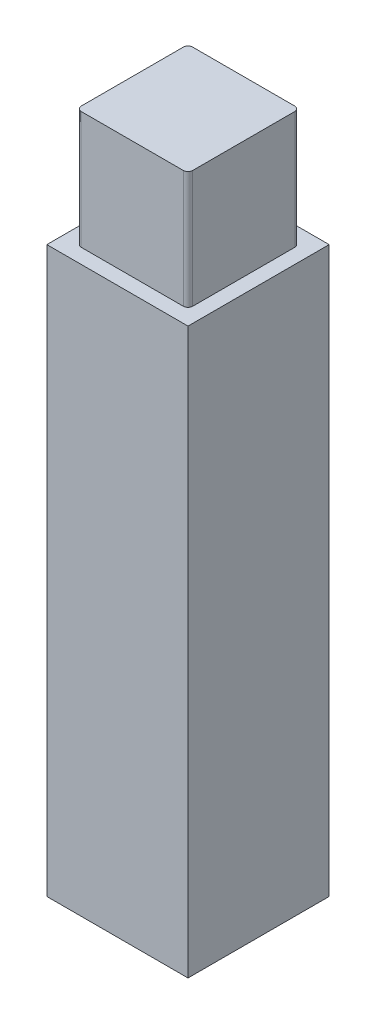
SolidWorks part; units mm, degrees
ref_plane "Front Plane" through (0, 0, 0) normal (0, 0, 1) x (1, 0, 0)
ref_plane "Top Plane" through (0, 0, 0) normal (0, 1, 0) x (1, 0, 0)
ref_plane "Right Plane" through (0, 0, 0) normal (1, 0, 0) x (0, 0, -1)
sketch "Sketch1" plane through (0, 0, 0) normal (0, 1, 0) x (1, 0, 0)
  line L1 (-15, 15) -> (15, 15)
  line L2 (-15, 15) -> (-15, -15)
  line L3 (-15, -15) -> (15, -15)
  line L4 (15, 15) -> (15, -15)
  line L5 (-15, 15) -> (15, -15) construction
  line L6 (-15, -15) -> (15, 15) construction
  point P0 (0, 0)
  dimension "D1" = 30
  dimension "D2" = 30
extrude "Boss-Extrude1" add sketch "Sketch1" along normal blind 120
sketch "Sketch2" plane through (0, 120, 0) normal (0, 1, 0) x (1, 0, 0)
  line L1 (-11.85, 11.85) -> (11.85, 11.85)
  line L2 (-11.85, 11.85) -> (-11.85, -11.85)
  line L3 (-11.85, -11.85) -> (11.85, -11.85)
  line L4 (11.85, 11.85) -> (11.85, -11.85)
  line L5 (-11.85, 11.85) -> (11.85, -11.85) construction
  line L6 (-11.85, -11.85) -> (11.85, 11.85) construction
  point P0 (0, 0)
  dimension "D1" = 23.7
  dimension "D2" = 23.7
extrude "Boss-Extrude2" add sketch "Sketch2" along normal blind 25
sketch "Sketch3" plane through (0, 0, 0) normal (0, -1, 0) x (1, 0, 0)
  line L1 (-12, 12) -> (12, 12)
  line L2 (-12, 12) -> (-12, -12)
  line L3 (-12, -12) -> (12, -12)
  line L4 (12, 12) -> (12, -12)
  line L5 (-12, 12) -> (12, -12) construction
  line L6 (-12, -12) -> (12, 12) construction
  point P0 (0, 0)
  dimension "D1" = 24
  dimension "D2" = 24
extrude "Cut-Extrude1" cut sketch "Sketch3" against normal blind 26
fillet "Fillet1" radius 1 4 edges at (-11.85, 132.5, -11.85) (-11.85, 132.5, 11.85) (11.85, 132.5, 11.85) (11.85, 132.5, -11.85)
equation "\"board_w\"= 33.8"
equation "\"board_l\"= 41"
equation "\"stack_h\"= 19.5"
equation "\"module_w\"= 9.9"
equation "\"lens_d\"= 7.8"
equation "\"lens_from_end\"= 8"
equation "\"usb_w\"= 13"
equation "\"plug_h\"= 7"
equation "\"usb_from_back\"= 6"
equation "\"clear\"= 0.4"
equation "\"wall\"= 3"
equation "\"floor_t\"= 2.5"
equation "\"pocket_clear\"= 0.3"
equation "\"lens_clear\"= 0.6"
equation "\"plate_w\"= 16"
equation "\"plate_clear\"= 0.3"
equation "\"plate_t\"= 1.2"
equation "\"plate_seat\"= 0.8"
equation "\"window_d\"= 12"
equation "\"lid_t\"= 2"
equation "\"lid_gap\"= 1"
equation "\"groove_d\"= 1.2"
equation "\"groove_clear\"= 0.15"
equation "\"lip_top\"= 1.2"
equation "\"side_clear\"= 0.2"
equation "\"slide_clear\"= 0.2"
equation "\"ball_d\"= 16"
equation "\"ball_clear\"= 0.3"
equation "\"lip\"= 1.2"
equation "\"cup_floor\"= 1.2"
equation "\"cup_d\"= 26"
equation "\"slit_w\"= 1.5"
equation "\"slit_depth\"= 9"
equation "\"lug_w\"= 16"
equation "\"m3_hole\"= 3.4"
equation "\"m3_nut\"= 5.7"
equation "\"m3_nut_d\"= 2.6"
equation "\"boss_d\"= 20"
equation "\"boss_h\"= 8"
equation "\"nut_af\"= 11.4"
equation "\"nut_t\"= 5.8"
equation "\"screw_hole\"= 6.6"
equation "\"post_w\"= 30"
equation "\"post_len\"= 120"
equation "\"spigot_w\"= 23.7"
equation "\"bore_w\"= 24"
equation "\"spigot_len\"= 25"
equation "\"base_w\"= 130"
equation "\"base_h\"= 40"
equation "\"hole_depth\"= 30"
equation "\"base_clear\"= 0.4"
equation "\"base_col\"= 42"
equation "\"base_shell\"= 3"
equation "\"head_h\"= 50"
equation "\"arm_under\"= 30"
equation "\"arm_reach\"= 45"
equation "\"face_run\"= 20"
equation "\"bb_d\"= 24"
equation "\"bb_h\"= 10"
equation "\"neck_d\"= 8"
equation "\"ball_drop\"= 14"
equation "\"in_l\"= \"board_l\" + 2 * \"clear\""
equation "\"in_w\"= \"board_w\" + 2 * \"clear\""
equation "\"out_l\"= \"in_l\" + 2 * \"wall\""
equation "\"out_w\"= \"in_w\" + 2 * \"wall\""
equation "\"y_groove\"= \"floor_t\" - \"plate_seat\" + \"stack_h\" + \"lid_gap\""
equation "\"groove_h\"= \"lid_t\" + 2 * \"groove_clear\""
equation "\"tray_h\"= \"y_groove\" + \"groove_h\" + \"lip_top\""
equation "\"lid_w\"= \"in_w\" + 2 * \"groove_d\" - 2 * \"side_clear\""
equation "\"lid_right\"= \"in_l\" / 2 + \"groove_d\" - \"slide_clear\""
equation "\"lid_left\"= \"out_l\" / 2"
equation "\"open_d\"= \"ball_d\" - 2 * \"lip\""
equation "\"c_ball\"= sqr( ( ( \"ball_d\" + \"ball_clear\" ) / 2 ) ^ 2 - ( \"open_d\" / 2 ) ^ 2 )"
equation "\"cup_h\"= \"cup_floor\" + ( \"ball_d\" + \"ball_clear\" ) / 2 + \"c_ball\""
equation "\"lug_in\"= \"cup_d\" / 2 - 5"
equation "\"lug_out\"= \"cup_d\" / 2 + 4"
equation "\"D1@Sketch1\"=\"post_w\""
equation "\"D1@Boss-Extrude1\"=\"post_len\""
equation "\"D1@Boss-Extrude2\"=\"spigot_len\""
equation "\"D2@Sketch3\"=\"bore_w\""
equation "\"D1@Cut-Extrude1\"=\"spigot_len\"+1"
